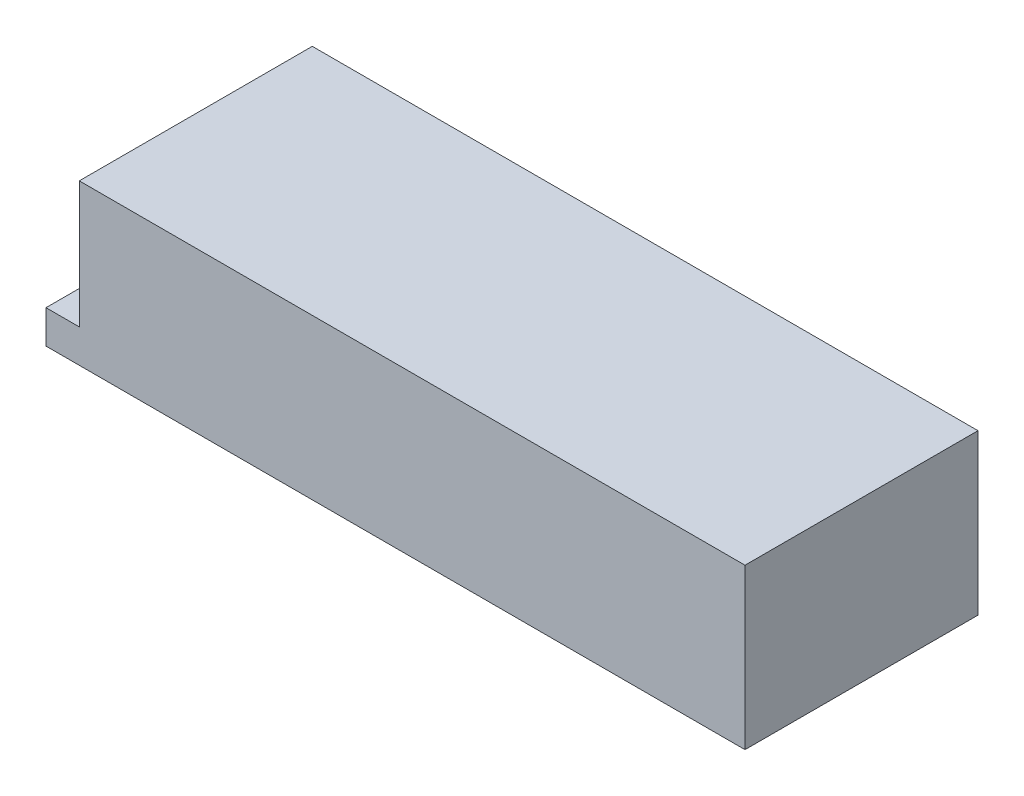
SolidWorks part; units mm, degrees
ref_plane "Front Plane" through (0, 0, 0) normal (0, 0, 1) x (1, 0, 0)
ref_plane "Top Plane" through (0, 0, 0) normal (0, 1, 0) x (1, 0, 0)
ref_plane "Right Plane" through (0, 0, 0) normal (1, 0, 0) x (0, 0, -1)
sketch "Sketch1" plane through (0, 0, 0) normal (0, 1, 0) x (1, 0, 0)
  line L1 (-67.6315, 58.2478) -> (32.3685, 58.2478)
  line L2 (-67.6315, 58.2478) -> (-67.6315, 23.2478)
  line L3 (-67.6315, 23.2478) -> (32.3685, 23.2478)
  line L4 (32.3685, 58.2478) -> (32.3685, 23.2478)
  dimension "D1" = 100
  dimension "D2" = 35
extrude "Extrude1" add sketch "Sketch1" along normal blind 24
sketch "Sketch2" plane through (-67.6315, 0, 0) normal (-1, 0, 0) x (0, 0, 1)
  line L0 (-23.2478, 24) -> (-23.2478, 0) construction
  line L1 (-58.2478, 0) -> (-23.2478, 0)
  line L2 (-58.2478, 0) -> (-58.2478, 5)
  line L3 (-58.2478, 5) -> (-23.2478, 5)
  line L4 (-23.2478, 0) -> (-23.2478, 5)
  dimension "D1" = 5
extrude "Extrude2" add sketch "Sketch2" along normal blind 5
